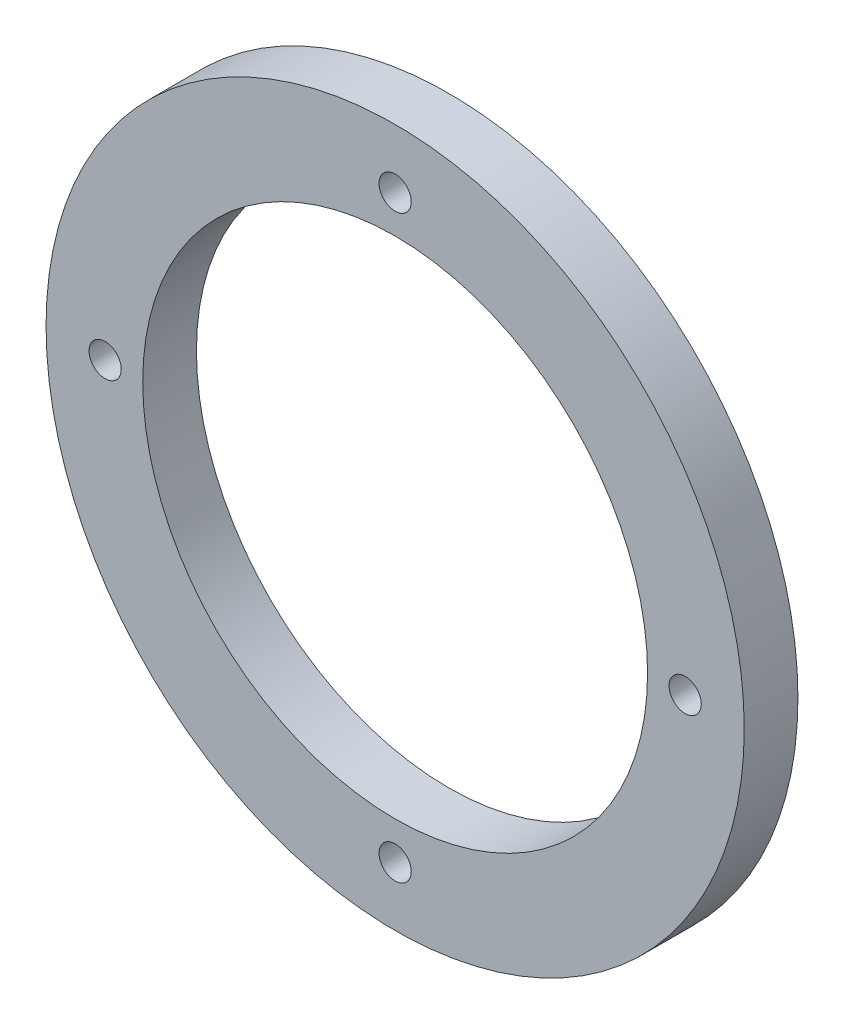
SolidWorks part; units mm, degrees
ref_plane "Front Plane" through (0, 0, 0) normal (0, 0, 1) x (1, 0, 0)
ref_plane "Top Plane" through (0, 0, 0) normal (0, 1, 0) x (1, 0, 0)
ref_plane "Right Plane" through (0, 0, 0) normal (1, 0, 0) x (0, 0, -1)
sketch "Sketch1" plane through (0, 0, 0) normal (0, 0, 1) x (1, 0, 0)
  circle A0 centre (0, 0) radius 32.5
  circle A1 centre (0, 0) radius 23.5
  circle A2 centre (-27, 0) radius 1.5
  circle A3 centre (27, 0) radius 1.5
  circle A4 centre (0, 27) radius 1.5
  circle A5 centre (0, -27) radius 1.5
  dimension "D1" = 65
  dimension "D2" = 47
  dimension "D3" = 3
  dimension "D4" = 3
  dimension "D5" = 3
  dimension "D6" = 3
  dimension "D7" = 27
  dimension "D8" = 27
  dimension "D9" = 27
  dimension "D10" = 27
extrude "Boss-Extrude1" add sketch "Sketch1" along normal blind 5
